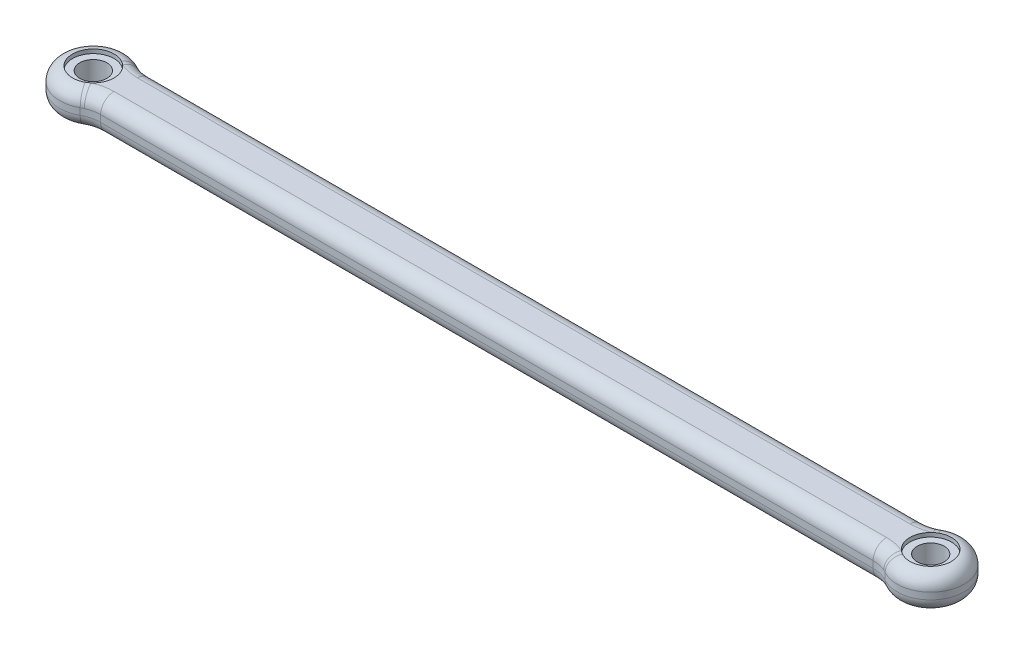
SolidWorks part; units mm, degrees
material "ABS PC"
ref_plane "Alzado" through (0, 0, 0) normal (1, 0, 0) x (0, 1, 0)
ref_plane "Planta" through (0, 0, 0) normal (0, 0, 1) x (0, 1, 0)
ref_plane "Vista lateral" through (0, 0, 0) normal (0, 1, 0) x (-1, 0, 0)
sketch "Croquis1" plane through (0, 0, 0) normal (0, 1, 0) x (-1, 0, 0)
  line L0 (0, 0) -> (250, 0) construction
  line L6 (6.6144, -7.5) -> (243.3856, -7.5)
  line L8 (243.3856, 7.5) -> (6.6144, 7.5)
  line L9 (125, -7.5) -> (125, 0) construction
  circle A0 centre (0, 0) radius 4.05 construction
  circle A1 centre (250, 0) radius 4.05 construction
  arc A2 (6.6144, 7.5) -> (6.6144, -7.5) centre (0, 0) ccw
  arc A3 (243.3856, -7.5) -> (260, 0) centre (250, 0) ccw construction
  arc A9 (243.3856, -7.5) -> (260, 0) centre (250, 0) ccw construction
  arc A10 (243.3856, -7.5) -> (243.3856, 7.5) centre (250, 0) ccw
  point P6 (0, 0)
  dimension "D3" = 8.1
  dimension "D4" = 20
  dimension "D1" = 250
  dimension "D2" = 15
extrude "Saliente-Extruir1" add sketch "Croquis1" along normal mid plane 10
sketch "Croquis2" plane through (0, 5, 0) normal (0, 1, 0) x (-1, 0, 0)
  point P0 (0, 0)
  point P1 (250, 0)
hole_wizard "Refrentado para tornillo con cabeza plana de M81" positions "Croquis2" profile "Croquis3" counterbore size "M8" standard "DIN" end condition through all
sketch "Croquis3" plane through (0, 5, 0) normal (1, 0, 0) x (0, 0, 1)
  line L0 (0, 0) -> (0, 10)
  line L1 (0, 10) -> (4.05, 10)
  line L3 (4.05, 10) -> (4.05, 1.2)
  line L4 (4.05, 1.2) -> (6.2, 1.2)
  line L5 (6.2, 1.2) -> (6.2, 0)
  line L7 (6.2, 0) -> (0, 0)
  line L11 (0, -6.35) -> (0, 107.95) construction
  dimension "Diámetro de taladro hasta el siguiente" = 8.1
  dimension "Profundidad de taladro hasta el siguiente" = 10
  dimension "Diámetro de refrentado" = 12.4
  dimension "Profundidad de refrentado" = 1.2
fillet "Redondeo7" radius 10 4 edges at (-243.3856, 0, 7.5) (-6.6144, 0, 7.5) (-243.3856, 0, -7.5) (-6.6144, 0, -7.5)
fillet "Redondeo6" radius 4 14 edges at (-260, -5, 0) (-125, 5, 7.5) (-125, -5, 7.5) (-125, 5, -7.5) (-125, -5, -7.5) (-7.1825, -5, -7.8175) (-7.1825, -5, 7.8175) (-242.8175, -5, 7.8175) (-242.8175, -5, -7.8175) (-7.1825, 5, -7.8175) (-7.1825, 5, 7.8175) (-242.8175, 5, 7.8175) (-242.8175, 5, -7.8175) (10, -5, 0)
equation "\"L1\"= 250"
equation "\"ancho\"= 15"
equation "\"esp\"= 10"
equation "\"agujeros\"=8.1"
equation "\"D1@Croquis1\"=\"L1\""
equation "\"D2@Croquis1\"=\"ancho\""
equation "\"D3@Croquis1\"=\"agujeros\""
equation "\"D1@Saliente-Extruir1\"=\"esp\""
